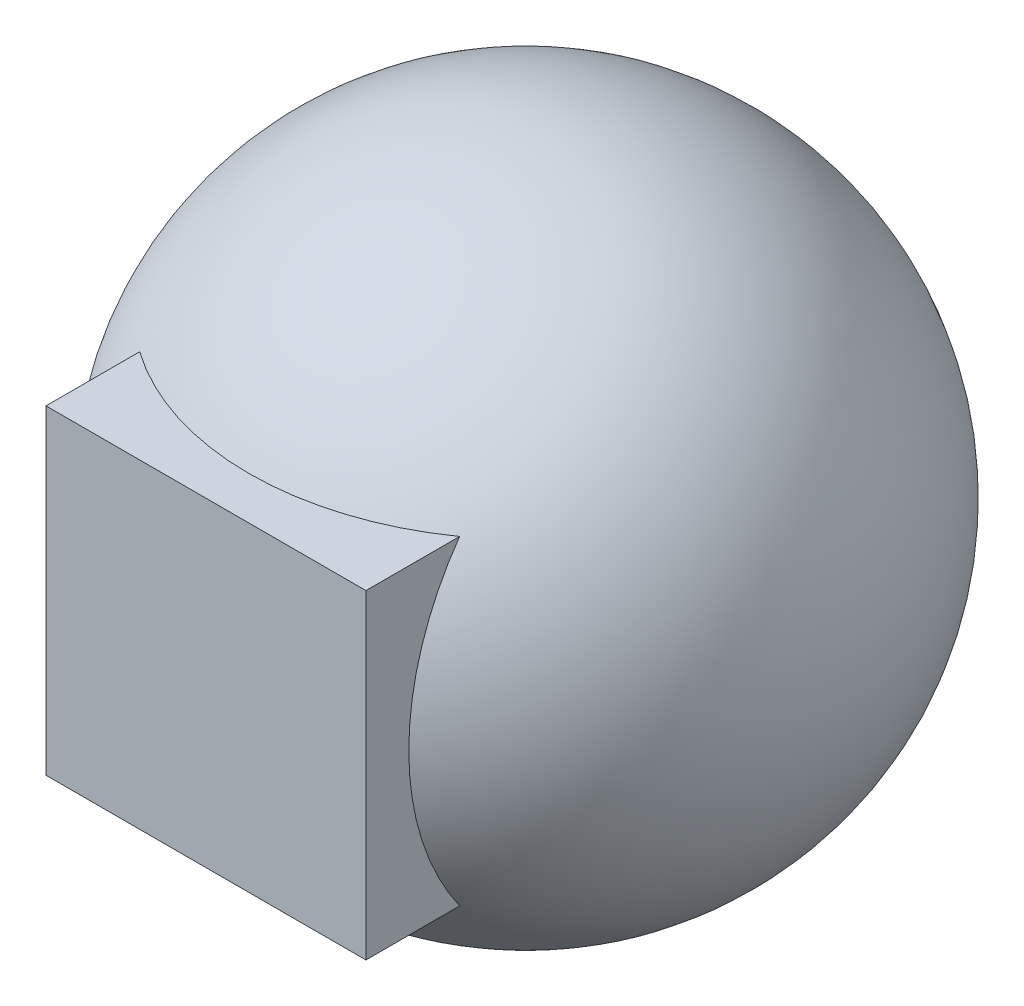
SolidWorks part; units mm, degrees
ref_plane "Alzado" through (0, 0, 0) normal (0, 0, 1) x (1, 0, 0)
ref_plane "Planta" through (0, 0, 0) normal (0, 1, 0) x (1, 0, 0)
ref_plane "Vista lateral" through (0, 0, 0) normal (1, 0, 0) x (0, 0, -1)
sketch "Croquis1" plane through (0, 0, 0) normal (0, 0, 1) x (1, 0, 0)
  line L0 (0, -20) -> (0, 20)
  arc A0 (0, -20) -> (0, 20) centre (0, 0) ccw
  dimension "D1" = 20
revolve "Revolución1" add sketch "Croquis1" angle 360 about L0
sketch "Croquis6" plane through (0, 0, 0) normal (0, 0, 1) x (1, 0, 0)
  line L1 (-10, -10) -> (10, -10)
  line L2 (-10, -10) -> (-10, 10)
  line L3 (-10, 10) -> (10, 10)
  line L4 (10, -10) -> (10, 10)
  line L5 (-10, -10) -> (10, 10) construction
  line L6 (-10, 10) -> (10, -10) construction
  point P0 (0, 0)
  dimension "D1" = 20
  dimension "D2" = 20
extrude "Saliente-Extruir2" add sketch "Croquis6" along normal blind 20
